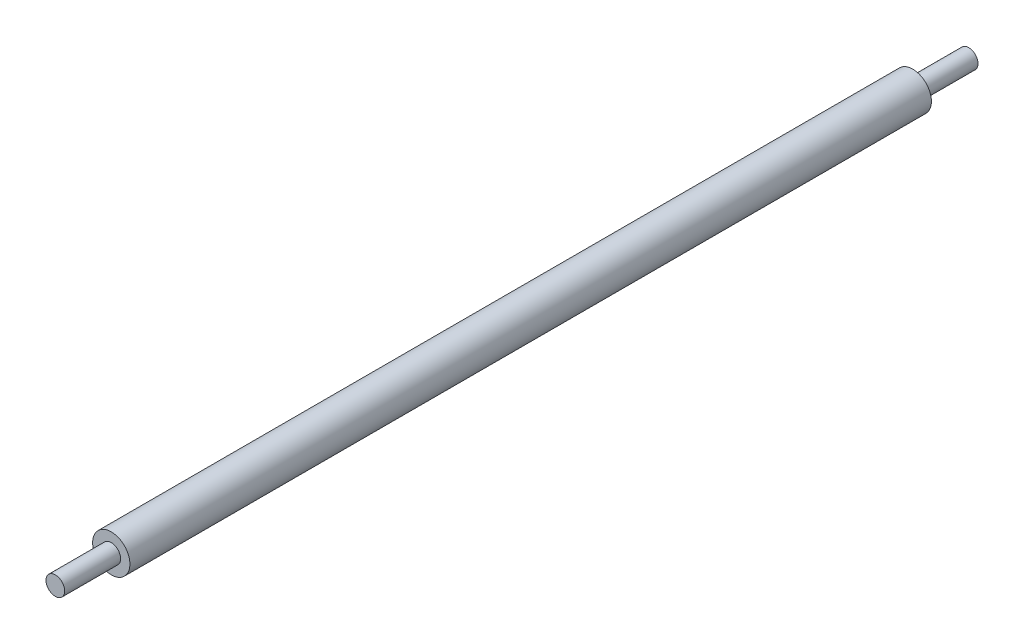
SolidWorks part; units mm, degrees
ref_plane "Front Plane" through (0, 0, 0) normal (0, 0, 1) x (1, 0, 0)
ref_plane "Top Plane" through (0, 0, 0) normal (0, 1, 0) x (1, 0, 0)
ref_plane "Right Plane" through (0, 0, 0) normal (1, 0, 0) x (0, 0, -1)
sketch "Sketch1" plane through (0, 0, 0) normal (0, 0, 1) x (1, 0, 0)
  circle A0 centre (0, 0) radius 12.7
extrude "Boss-Extrude1" add sketch "Sketch1" along normal blind 622.3 contours A0
sketch "Sketch2" plane through (0, 0, 0) normal (0, 0, 1) x (1, 0, 0)
  circle A0 centre (0, 0) radius 6.3619
extrude "Cut-Extrude1" cut sketch "Sketch2" along normal blind 38.1 flip side to cut contours A0
sketch "Sketch5" plane through (0, 0, 622.3) normal (0, 0, 1) x (1, 0, 0)
  circle A0 centre (0, 0) radius 6.3779
extrude "Cut-Extrude4" cut sketch "Sketch5" against normal blind 38.1 flip side to cut
